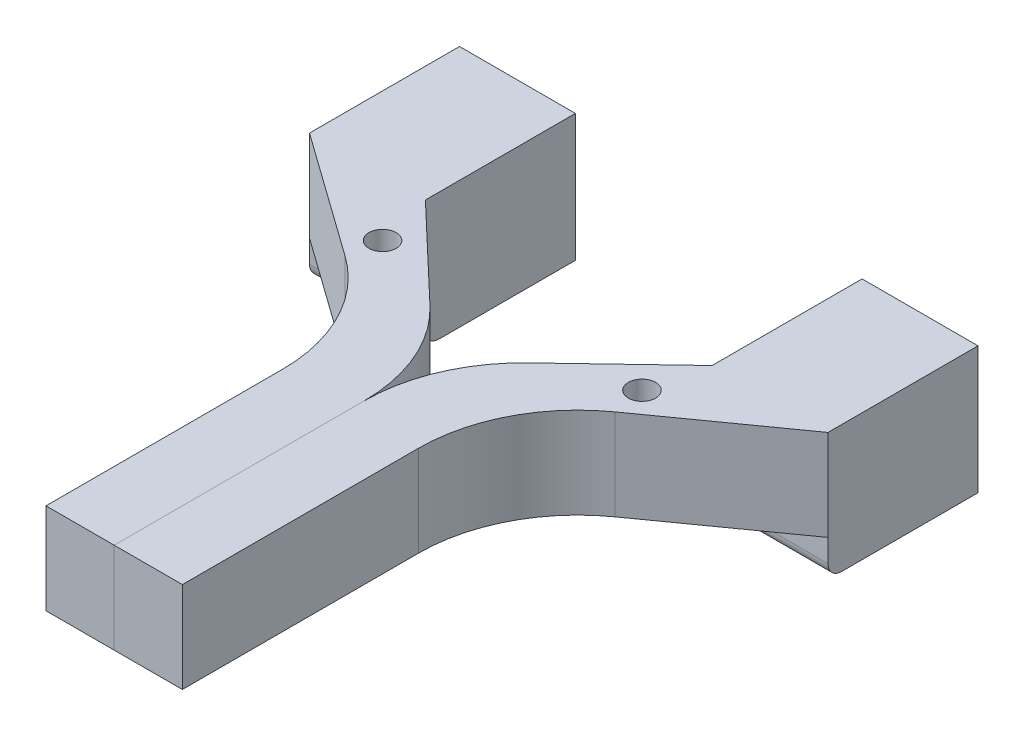
SolidWorks part; units mm, degrees
ref_plane "정면" through (0, 0, 0) normal (0, 0, 1) x (1, 0, 0)
ref_plane "윗면" through (0, 0, 0) normal (0, 1, 0) x (1, 0, 0)
ref_plane "우측면" through (0, 0, 0) normal (1, 0, 0) x (0, 0, -1)
sketch "스케치1" plane through (0, 0, 0) normal (0, 0, 1) x (1, 0, 0)
  line L1 (-6.25, -11.3) -> (6.25, -11.3)
  line L2 (-6.25, -11.3) -> (-6.25, 11.3)
  line L3 (-6.25, 11.3) -> (6.25, 11.3)
  line L4 (6.25, -11.3) -> (6.25, 11.3)
  line L5 (-6.25, -11.3) -> (6.25, 11.3) construction
  line L6 (-6.25, 11.3) -> (6.25, -11.3) construction
  line L7 (-16.25, -14) -> (9.25, -14)
  line L8 (-16.25, -14) -> (-16.25, 14)
  line L9 (-16.25, 14) -> (9.25, 14)
  line L10 (9.25, -14) -> (9.25, 14)
  line L11 (-16.25, -14) -> (9.25, 14) construction
  line L12 (-16.25, 14) -> (9.25, -14) construction
  point P0 (0, 0)
  point P6 (-3.5, 0)
  point P7 (0, 0)
  dimension "D1" = 12.5
  dimension "D2" = 22.6
  dimension "D3" = 3
  dimension "D4" = 10
  dimension "D5" = 28
  dimension "D6" = 0
extrude "보스-돌출1" add sketch "스케치1" along normal blind 30
sketch "스케치2" plane through (0, 0, 30) normal (0, 0, 1) x (1, 0, 0)
  line L1 (9.25, 14) -> (-16.25, 14)
  line L2 (9.25, 14) -> (9.25, -14)
  line L3 (9.25, -14) -> (-16.25, -14)
  line L4 (-16.25, 14) -> (-16.25, -14)
extrude "보스-돌출2" add sketch "스케치2" along normal blind 3
sketch "스케치7" plane through (0, 14, 0) normal (0, 1, 0) x (1, 0, 0)
  line L0 (9.25, -33) -> (40.7846, -63)
  line L1 (-16.25, -33) -> (25.7846, -63)
  line L2 (25.7846, -63) -> (25.7846, -133)
  line L3 (25.7846, -133) -> (40.7846, -133)
  line L4 (40.7846, -133) -> (40.7846, -63)
  line L6 (9.25, -33) -> (-16.25, -33)
  dimension "D1" = 15
  dimension "D2" = 30
  dimension "D3" = 30
  dimension "D4" = 70
extrude "보스-돌출4" add sketch "스케치7" against normal blind 20
fillet "필렛5" radius 3 1 edges at (-3.5, -14, 33)
fillet "필렛7" radius 35 2 edges at (40.7846, 4, 63) (25.7846, 4, 63)
sketch "스케치8" plane through (0, 14, 0) normal (0, 1, 0) x (1, 0, 0)
  line L0 (12.25, 3.0467) -> (12.25, -21.6558) construction
  line L1 (12.25, -21.6558) -> (12.25, -69.1964) construction
  line L2 (9.25, -33) -> (9.25, 0) construction
  circle A0 centre (12.25, -45.4261) radius 3
  dimension "D1" = 3
extrude "컷-돌출1" cut sketch "스케치8" against normal blind 30
mirror "대칭 복사3" about plane through (40.7846, -6, 133) normal (1, 0, 0) of bodies 115
other "바디 저장2"
